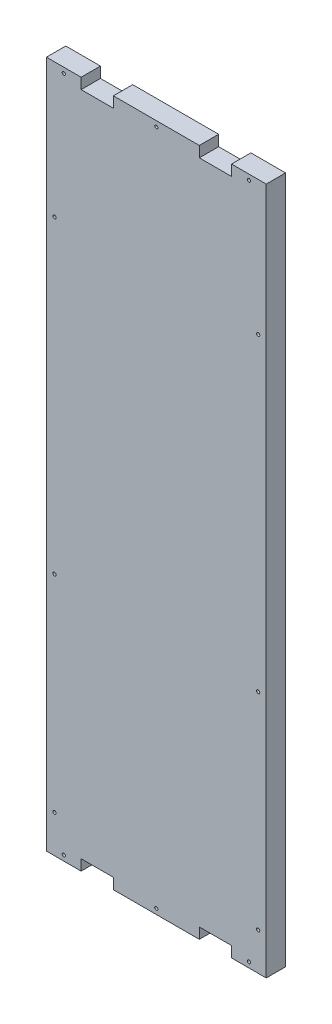
SolidWorks part; units mm, degrees
ref_plane "Front Plane" through (0, 0, 0) normal (0, 0, 1) x (1, 0, 0)
ref_plane "Top Plane" through (0, 0, 0) normal (0, 1, 0) x (1, 0, 0)
ref_plane "Right Plane" through (0, 0, 0) normal (1, 0, 0) x (0, 0, -1)
sketch "Sketch1" plane through (0, 0, 0) normal (0, 0, 1) x (1, 0, 0)
  line L0 (212, -36.5) -> (-18, -36.5) construction
  line L1 (-5.3, -36.5) -> (199.3, -36.5)
  line L2 (-5.3, -36.5) -> (-5.3, 603.5)
  line L3 (-5.3, 603.5) -> (199.3, 603.5)
  line L4 (199.3, -36.5) -> (199.3, 603.5)
  dimension "D1" = 640
extrude "Boss-Extrude1" add sketch "Sketch1" along normal blind 18
hole_wizard "Ø3.0 (3) Diameter Hole1" positions "Sketch2" profile "Sketch3" hole size "Ø3.0" standard "ISO"
sketch "Sketch2" plane through (0, 0, 0) normal (0, 0, -1) x (-1, 0, 0)
  line L0 (-20.2, 476.25) -> (-20.2, 478.5) construction
  line L1 (-21.45, 476.25) -> (-18.95, 476.25) construction
  line L2 (-20.2, 478.5) -> (-23.7, 478.5) construction
  line L3 (-173.8, 476.25) -> (-173.8, 480.75) construction
  line L4 (-172.55, 476.25) -> (-175.05, 476.25) construction
  line L5 (-175.05, 480.75) -> (-172.55, 480.75) construction
  line L7 (-173.8, 192.75) -> (-173.8, 188.25) construction
  line L8 (-175.05, 192.75) -> (-172.55, 192.75) construction
  line L10 (-172.55, 188.25) -> (-175.05, 188.25) construction
  line L11 (-20.2, -3.75) -> (-20.2, 0.75) construction
  line L12 (-21.45, -3.75) -> (-18.95, -3.75) construction
  line L13 (-18.95, 0.75) -> (-21.45, 0.75) construction
  line L14 (-173.8, -3.75) -> (-173.8, 0.75) construction
  line L15 (-172.55, -3.75) -> (-175.05, -3.75) construction
  line L16 (-175.05, 0.75) -> (-172.55, 0.75) construction
  point P2 (-20.2, 478.5)
  point P13 (-173.8, 478.5)
  point P37 (-173.8, 190.5)
  point P39 (-20.2, 190.5)
  point P50 (-20.2, -1.5)
  point P60 (-173.8, -1.5)
  point P61 (-131.9476, 597.7732)
  point P64 (-61.0278, 597.7732)
  point P67 (-131.9476, -30.5832)
  point P69 (-61.0278, -30.5832)
sketch "Sketch3" plane through (61.0278, -30.5832, 0) normal (1, 0, 0) x (0, 1, 0)
  line L0 (0, 0) -> (0, 5.9013)
  line L1 (0, 5.9013) -> (1.5, 5)
  line L2 (1.5, 5) -> (1.5, 0)
  line L5 (1.5, 0) -> (0, 0)
  line L10 (0, 5.9013) -> (-1.5, 5) construction
  line L11 (0, -6.35) -> (0, 107.95) construction
  dimension "Hole Dia." = 3
  dimension "Hole Depth" = 5
  dimension "Drill Angle" = 118
sketch "Sketch4" plane through (0, 0, 0) normal (0, 0, -1) x (-1, 0, 0)
  line L0 (5.3, -36.5) -> (5.3, 603.5) construction
  line L1 (-27, -36.5) -> (-57, -36.5)
  line L2 (-27, -36.5) -> (-27, -26.5)
  line L3 (-27, -26.5) -> (-57, -26.5)
  line L4 (-57, -36.5) -> (-57, -26.5)
  line L5 (5.3, 283.5) -> (-199.3, 283.5) construction
  line L6 (5.3, -15.2275) -> (-199.3, -15.2275) construction
  line L15 (5.3, 603.5) -> (5.3, -36.5) construction
  line L16 (-199.3, -36.5) -> (-199.3, 603.5) construction
  line L17 (-137, -36.5) -> (-137, -26.5)
  line L18 (-97, -15.2275) -> (-97, -26.5) construction
  line L19 (-167, -26.5) -> (-137, -26.5)
  line L20 (-167, -36.5) -> (-167, -26.5)
  line L21 (-167, -36.5) -> (-137, -36.5)
  line L22 (-57, 603.5) -> (-57, 593.5)
  line L23 (-27, 593.5) -> (-57, 593.5)
  line L24 (-27, 603.5) -> (-27, 593.5)
  line L25 (-27, 603.5) -> (-57, 603.5)
  line L26 (-167, 603.5) -> (-137, 603.5)
  line L27 (-167, 603.5) -> (-167, 593.5)
  line L28 (-167, 593.5) -> (-137, 593.5)
  line L29 (-137, 603.5) -> (-137, 593.5)
  dimension "D1" = 30
  dimension "D2" = 40
extrude "Cut-Extrude1" cut sketch "Sketch4" against normal blind 18
hole_wizard "Ø3.0 (3) Diameter Hole3" positions "Sketch9" profile "Sketch10" hole size "Ø3.0" standard "ISO" end condition through all
sketch "Sketch9" plane through (0, 0, 0) normal (0, 0, -1) x (-1, 0, 0)
  line L0 (-2.2, -3.75) -> (-2.2, 0.75) construction
  line L1 (-3.45, -3.75) -> (-0.95, -3.75) construction
  line L2 (-0.95, 0.75) -> (-3.45, 0.75) construction
  line L4 (-191.8, -3.75) -> (-191.8, 0.75) construction
  line L5 (-193.05, -3.75) -> (-190.55, -3.75) construction
  line L6 (-190.55, 0.75) -> (-193.05, 0.75) construction
  line L8 (-191.8, 188.25) -> (-191.8, 192.75) construction
  line L9 (-193.05, 188.25) -> (-190.55, 188.25) construction
  line L10 (-190.55, 192.75) -> (-193.05, 192.75) construction
  line L12 (-191.8, 476.25) -> (-191.8, 480.75) construction
  line L13 (-193.05, 476.25) -> (-190.55, 476.25) construction
  line L14 (-190.55, 480.75) -> (-193.05, 480.75) construction
  line L17 (-2.2, 476.25) -> (-2.2, 480.75) construction
  line L18 (-3.45, 476.25) -> (-0.95, 476.25) construction
  line L19 (-0.95, 480.75) -> (-3.45, 480.75) construction
  line L21 (-2.2, 188.25) -> (-2.2, 192.75) construction
  line L22 (-3.45, 188.25) -> (-0.95, 188.25) construction
  line L23 (-0.95, 192.75) -> (-3.45, 192.75) construction
  point P12 (-2.2, -1.5)
  point P23 (-191.8, -1.5)
  point P34 (-191.8, 190.5)
  point P45 (-191.8, 478.5)
  point P59 (-2.2, 478.5)
  point P69 (-2.2, 190.5)
sketch "Sketch10" plane through (2.2, 190.5, 0) normal (1, 0, 0) x (0, 1, 0)
  line L0 (0, 0) -> (0, 18)
  line L1 (0, 18) -> (1.5, 18)
  line L2 (1.5, 18) -> (1.5, 0)
  line L5 (1.5, 0) -> (0, 0)
  line L11 (0, -6.35) -> (0, 107.95) construction
  dimension "Thru Hole Dia." = 3
  dimension "Thru Hole Depth" = 18
hole_wizard "Ø3.0 (3) Diameter Hole5" positions "Sketch12" profile "Sketch11" hole size "Ø3.0" standard "ISO" end condition through all
sketch "Sketch12" plane through (0, 0, 0) normal (0, 0, -1) x (-1, 0, 0)
  line L0 (-57, -31.5) -> (-137, -31.5) construction
  line L1 (-57, -26.5) -> (-57, -36.5) construction
  line L2 (-137, -36.5) -> (-137, -26.5) construction
  line L4 (-167, -31.5) -> (-199.3, -31.5) construction
  line L5 (-167, -26.5) -> (-167, -36.5) construction
  line L6 (-199.3, -36.5) -> (-199.3, 603.5) construction
  line L8 (-27, -31.5) -> (5.3, -31.5) construction
  line L9 (-27, -36.5) -> (-27, -26.5) construction
  line L10 (5.3, 603.5) -> (5.3, -36.5) construction
  line L12 (-199.3, 283.5) -> (5.3, 283.5) construction
  line L14 (-27, 598.5) -> (5.3, 598.5) construction
  line L15 (-167, 598.5) -> (-199.3, 598.5) construction
  line L16 (-57, 598.5) -> (-137, 598.5) construction
  point P0 (238.5366, 43.355)
  point P1 (-97, -31.5)
  point P3 (-183.15, -31.5)
  point P5 (-10.85, -31.5)
  point P36 (-97, -31.5)
  point P45 (-183.15, -31.5)
  point P47 (-10.85, -31.5)
  point P54 (-10.85, 598.5)
  point P55 (-183.15, 598.5)
  point P56 (-97, 598.5)
sketch "Sketch11" plane through (-238.5366, 43.355, 0) normal (1, 0, 0) x (0, 1, 0)
  line L0 (0, 0) -> (0, 18)
  line L1 (0, 18) -> (1.5, 18)
  line L2 (1.5, 18) -> (1.5, 0)
  line L5 (1.5, 0) -> (0, 0)
  line L11 (0, -6.35) -> (0, 107.95) construction
  dimension "Thru Hole Dia." = 3
  dimension "Thru Hole Depth" = 18
